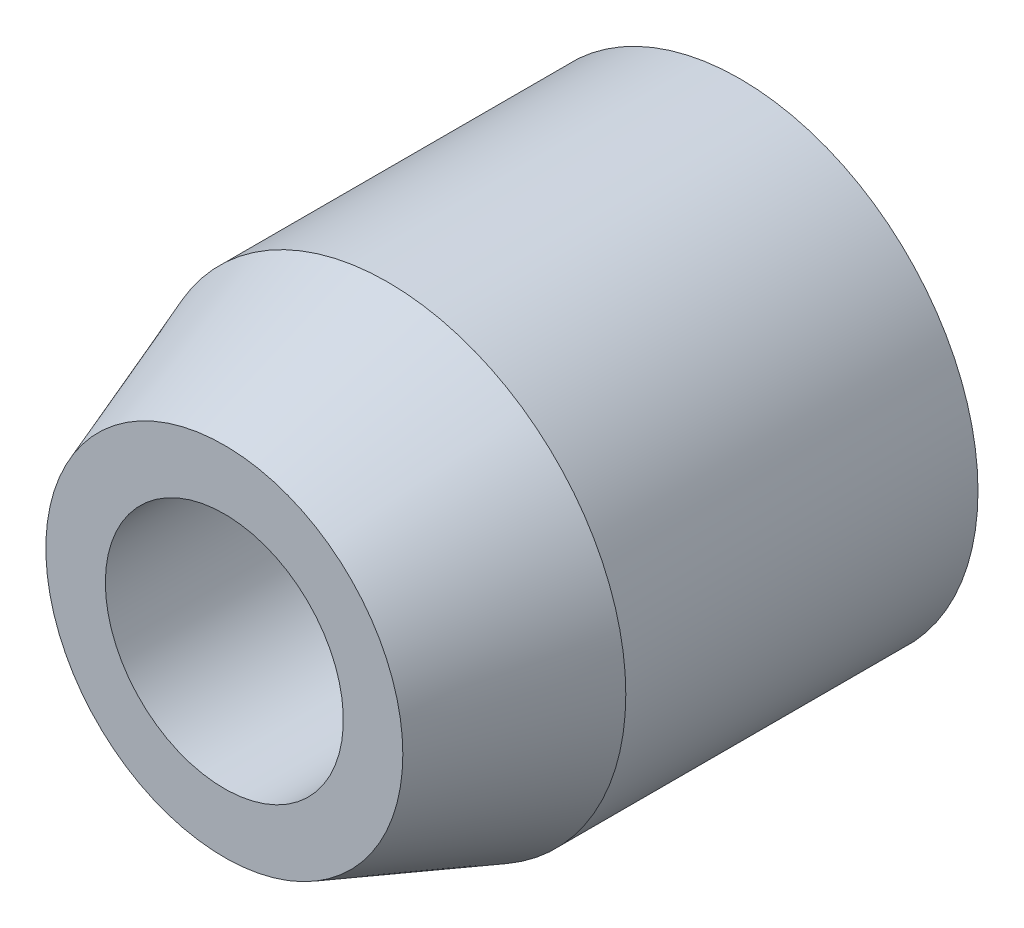
SolidWorks part; units mm, degrees
material "Brass"
ref_plane "Front Plane" through (0, 0, 0) normal (0, 0, 1) x (1, 0, 0)
ref_plane "Top Plane" through (0, 0, 0) normal (0, 1, 0) x (1, 0, 0)
ref_plane "Right Plane" through (0, 0, 0) normal (1, 0, 0) x (0, 0, -1)
sketch "Croquis2" plane through (0, 0, 0) normal (0, 0, 1) x (1, 0, 0)
  circle A0 centre (0, 0) radius 6
  circle A1 centre (0, 0) radius 3
extrude "Saliente-Extruir1" add sketch "Croquis2" along normal blind 13
sketch "Croquis3" plane through (0, 0, 13) normal (0, 0, 1) x (1, 0, 0)
  circle A0 centre (0, 0) radius 4.5
extrude "Cortar-Extruir3" cut sketch "Croquis3" against normal blind 5 draft 20 flip side to cut
